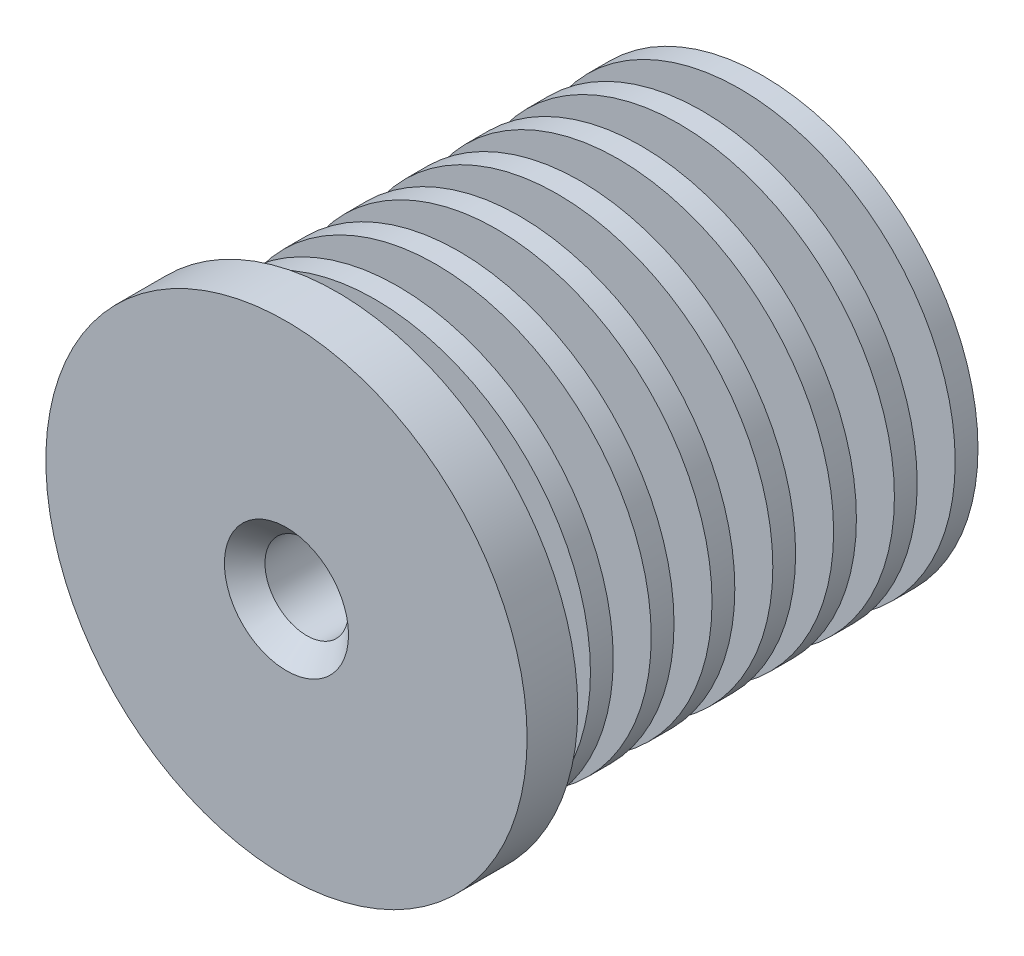
SolidWorks part; units mm, degrees
material "1060 Alloy"
ref_plane "Front Plane" through (0, 0, 0) normal (0, 0, 1) x (1, 0, 0)
ref_plane "Top Plane" through (0, 0, 0) normal (0, 1, 0) x (1, 0, 0)
ref_plane "Right Plane" through (0, 0, 0) normal (1, 0, 0) x (0, 0, -1)
sketch "Sketch2" plane through (0, 0, 0) normal (0, 1, 0) x (1, 0, 0)
  line L0 (0, 0) -> (0, 11.6) construction
  line L1 (1.65, 18.8) -> (1.65, 0)
  line L4 (9.5, 2) -> (6, 2)
  line L5 (6, 2) -> (6, 3.5)
  line L6 (6, 3.5) -> (8.5, 3.5)
  line L7 (8.5, 3.5) -> (8.5, 4.4)
  line L8 (8.5, 4.4) -> (3.5, 4.4)
  line L9 (3.5, 4.4) -> (3.5, 5.9)
  line L10 (3.5, 5.9) -> (8.5, 5.9)
  line L11 (8.5, 5.9) -> (8.5, 6.8)
  line L12 (8.5, 6.8) -> (3.5, 6.8)
  line L13 (3.5, 6.8) -> (3.5, 8.3)
  line L14 (3.5, 8.3) -> (8.5, 8.3)
  line L15 (8.5, 8.3) -> (8.5, 9.2)
  line L16 (8.5, 9.2) -> (3.5, 9.2)
  line L17 (3.5, 9.2) -> (3.5, 10.7)
  line L18 (3.5, 10.7) -> (8.5, 10.7)
  line L19 (8.5, 10.7) -> (8.5, 11.6)
  line L20 (8.5, 11.6) -> (3.5, 11.6)
  line L21 (1.65, 0) -> (9.5, 0)
  line L22 (9.5, 0) -> (9.5, 2)
  line L23 (3.5, 11.6) -> (3.5, 13.1)
  line L24 (3.5, 13.1) -> (8.5, 13.1)
  line L25 (8.5, 13.1) -> (8.5, 14)
  line L26 (8.5, 14) -> (3.5, 14)
  line L27 (3.5, 14) -> (3.5, 15.5)
  line L28 (3.5, 15.5) -> (8.5, 15.5)
  line L29 (8.5, 15.5) -> (8.5, 16.4)
  line L30 (8.5, 16.4) -> (3.5, 16.4)
  line L31 (3.5, 16.4) -> (3.5, 17.9)
  line L32 (3.5, 17.9) -> (8.5, 17.9)
  line L33 (8.5, 17.9) -> (8.5, 18.8)
  line L34 (8.5, 18.8) -> (1.65, 18.8)
  dimension "D1" = 17
  dimension "D2" = 0.9
  dimension "D3" = 0.9
  dimension "D4" = 3.3
  dimension "D5" = 7
  dimension "D6" = 12
  dimension "D7" = 19
  dimension "D8" = 1.5
  dimension "D9" = 2
revolve "Revolve1" add sketch "Sketch2" angle 360 about L0
cosmetic thread "Cosmetic Thread1" parameters "D2"=4
chamfer "Chamfer1" distance 0.8 angle 45 1 edges at (1.65, 0, 0)
sketch "Sketch4" plane through (0, 0, 0) normal (0, 1, 0) x (1, 0, 0)
  line L0 (0, 18.8) -> (0, 7.5296) construction
  line L1 (8.5, 18.8) -> (-8.5, 18.8) construction
  line L2 (0, 7.5296) -> (1.65, 7.5296)
  line L3 (1.65, 0.8) -> (1.65, 18.8) construction
  line L4 (1.65, 7.5296) -> (2.1, 7.8)
  line L5 (2.1, 7.8) -> (2.1, 11.5597)
  line L6 (2.1, 11.5597) -> (2.5, 11.8)
  line L7 (2.5, 11.8) -> (2.5, 18.8)
  line L8 (2.5, 18.8) -> (0, 18.8)
  line L9 (2.1, 11.5597) -> (0, 10.2978) construction
  line L10 (0, 18.8) -> (0, 7.5296)
  dimension "D1" = 4.2
  dimension "D2" = 59
  dimension "D4" = 5
  dimension "D5" = 7
  dimension "D3" = 11
revolve "Cut-Revolve1" cut sketch "Sketch4" angle 360 about L10
cosmetic thread "Cosmetic Thread2" parameters "D1"=6, "D2"=6
equation "\"D2@Sketch4\"=118/2"
